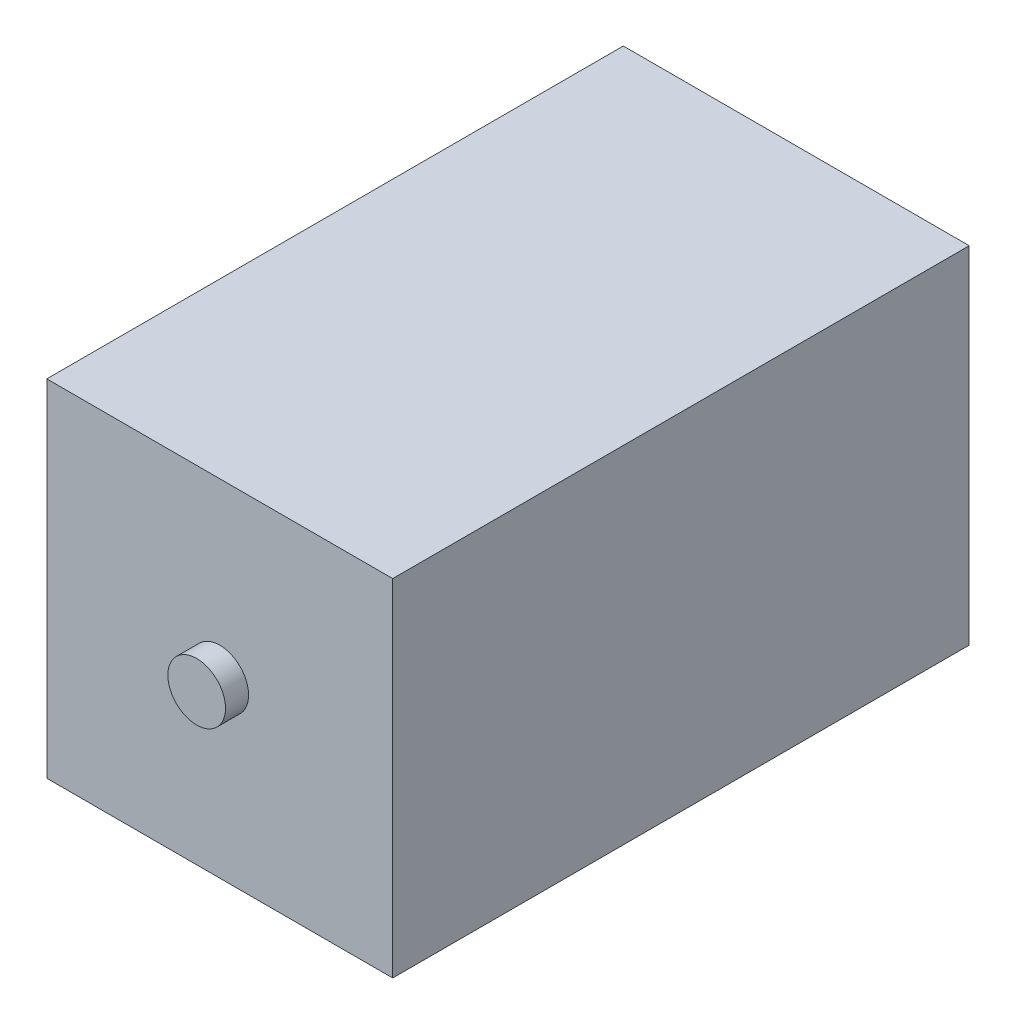
SolidWorks part; units mm, degrees
ref_plane "Front Plane" through (0, 0, 0) normal (0, 0, 1) x (1, 0, 0)
ref_plane "Top Plane" through (0, 0, 0) normal (0, 1, 0) x (1, 0, 0)
ref_plane "Right Plane" through (0, 0, 0) normal (1, 0, 0) x (0, 0, -1)
sketch "Sketch1" plane through (0, 0, 0) normal (0, 0, 1) x (1, 0, 0)
  line L0 (0, 0) -> (0, 150)
  line L1 (0, 0) -> (150, 0)
  line L2 (0, 150) -> (150, 150)
  line L3 (150, 0) -> (150, 150)
  dimension "D1" = 150
extrude "Boss-Extrude1" add sketch "Sketch1" along normal blind 250
sketch "Sketch2" plane through (0, 0, 250) normal (0, 0, 1) x (1, 0, 0)
  line L0 (0, 150) -> (150, 0) construction
  circle A0 centre (75, 75) radius 12.5
  point P6 (75, 75)
  dimension "D1" = 25
extrude "Boss-Extrude2" add sketch "Sketch2" along normal blind 10
